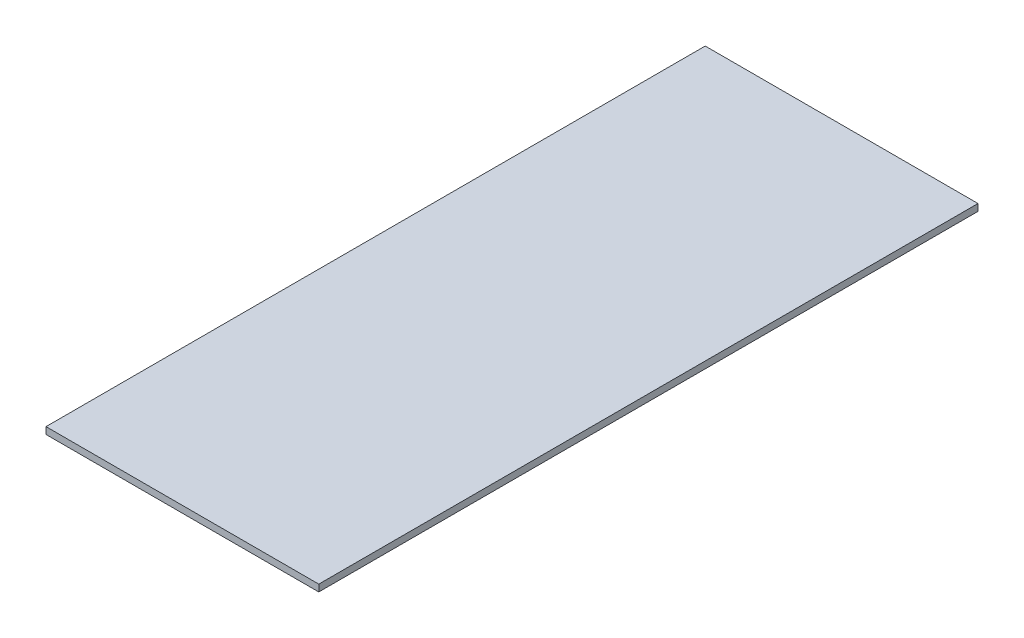
SolidWorks part; units mm, degrees
ref_plane "前视基准面" through (0, 0, 0) normal (0, 0, 1) x (1, 0, 0)
ref_plane "上视基准面" through (0, 0, 0) normal (0, 1, 0) x (1, 0, 0)
ref_plane "右视基准面" through (0, 0, 0) normal (1, 0, 0) x (0, 0, -1)
other "Configuration Table"
sketch "草图1" plane through (0, 0, 0) normal (0, 1, 0) x (1, 0, 0)
  line L1 (-44.0405, 45.3473) -> (75.9595, 45.3473)
  line L2 (-44.0405, 45.3473) -> (-44.0405, -244.6527)
  line L3 (-44.0405, -244.6527) -> (75.9595, -244.6527)
  line L4 (75.9595, 45.3473) -> (75.9595, -244.6527)
  dimension "D1" = 290
  dimension "D2" = 120
extrude "凸台-拉伸1" add sketch "草图1" along normal blind 3
